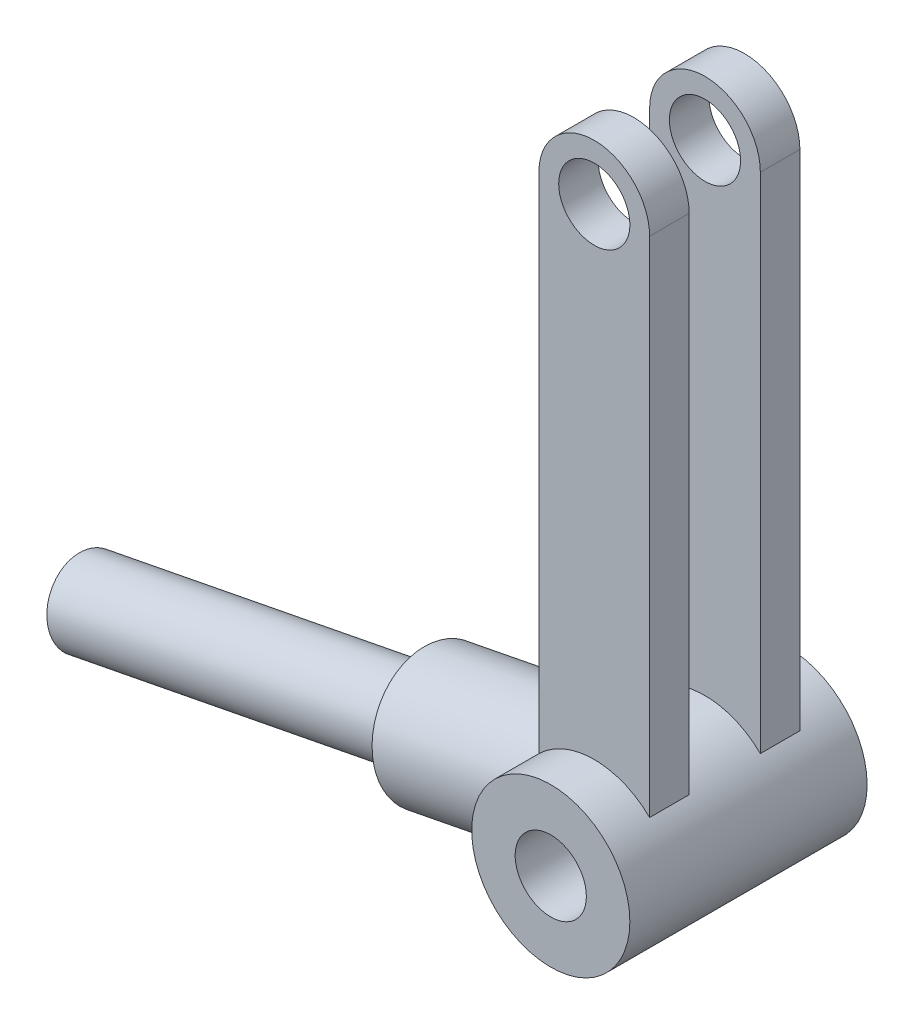
SolidWorks part; units mm, degrees
ref_plane "前视基准面" through (0, 0, 0) normal (0, 0, 1) x (1, 0, 0)
ref_plane "上视基准面" through (0, 0, 0) normal (0, 1, 0) x (1, 0, 0)
ref_plane "右视基准面" through (0, 0, 0) normal (1, 0, 0) x (0, 0, -1)
sketch "草图1" plane through (0, 0, 0) normal (0, 0, 1) x (1, 0, 0)
  circle A0 centre (0, 0) radius 10
  dimension "D1" = 20
extrude "凸台-拉伸1" add sketch "草图1" along normal blind 30
sketch "草图2" plane through (0, 0, 30) normal (0, 0, 1) x (1, 0, 0)
  circle A0 centre (0, 0) radius 4.5
  dimension "D1" = 9
extrude "切除-拉伸1" cut sketch "草图2" against normal blind 30
sketch "草图3" plane through (0, 0, 0) normal (0, 1, 0) x (1, 0, 0)
  line L0 (10, -15) -> (-10, -15) construction
  line L1 (10, -30) -> (10, 0) construction
  line L2 (-10, 0) -> (-10, -30) construction
  line L3 (0, -19.5) -> (7, -19.5)
  line L4 (0, -19.5) -> (-7, -19.5)
  line L5 (0, -10.5) -> (7, -10.5)
  line L6 (0, -10.5) -> (-7, -10.5)
  line L7 (7, -10.5) -> (7, -5.5)
  line L8 (7, -5.5) -> (-7, -5.5)
  line L9 (-7, -5.5) -> (-7, -10.5)
  line L15 (7, -19.5) -> (7, -24.5)
  line L16 (-7, -24.5) -> (-7, -19.5)
  line L17 (7, -24.5) -> (-7, -24.5)
  dimension "D1" = 14
  dimension "D5" = 5
extrude "凸台-拉伸2" add sketch "草图3" along normal blind 66.3 from offset 4.5
sketch "草图4" plane through (0, 0, 5.5) normal (0, 0, -1) x (-1, 0, 0)
  line L0 (-7, 70.8) -> (7, 70.8) construction
  line L1 (-7, 70.8) -> (7, 70.8)
  arc A0 (7, 70.8) -> (-7, 70.8) centre (0, 70.8) ccw
extrude "凸台-拉伸3" add sketch "草图4" against normal blind 5
sketch "草图5" plane through (0, 0, 24.5) normal (0, 0, 1) x (1, 0, 0)
  line L0 (-7, 70.8) -> (7, 70.8) construction
  line L1 (-7, 70.8) -> (7, 70.8)
  arc A0 (7, 70.8) -> (-7, 70.8) centre (0, 70.8) ccw
extrude "凸台-拉伸4" add sketch "草图5" against normal blind 5
sketch "草图6" plane through (0, 0, 5.5) normal (0, 0, -1) x (-1, 0, 0)
  line L0 (-7, 70.8) -> (7, 70.8) construction
  circle A0 centre (0, 70.8) radius 4.5
  dimension "D1" = 9
extrude "切除-拉伸2" cut sketch "草图6" against normal blind 27
sketch "草图14" plane through (0, 0, 5.5) normal (0, 0, -1) x (-1, 0, 0)
  line L2 (4.4175, -0.8579) -> (5.9426, 6.9954)
  line L3 (5.9426, 6.9954) -> (11.3417, 5.9469)
  line L5 (9.8166, -1.9064) -> (11.3417, 5.9469)
  line L6 (4.4175, -0.8579) -> (9.8166, -1.9064)
  circle A2 centre (0, 0) radius 10 construction
  arc A3 (9.8166, -1.9064) -> (7.4151, 6.7095) centre (0, 0) ccw
ref_plane "基准面1" through (0, 0, 15) normal (0, 0, 1) x (1, 0, 0)
sketch "草图15" plane through (0, 0, 15) normal (0, 0, 1) x (1, 0, 0)
  line L1 (-4.4175, -0.8579) -> (-5.9426, 6.9954) construction
  line L5 (-4.4175, -0.8579) -> (-5.9426, 6.9954)
  line L12 (-4.4175, -0.8579) -> (-29.4498, -5.7191)
  line L13 (-5.9426, 6.9954) -> (-30.9749, 2.1342)
  line L14 (-29.4498, -5.7191) -> (-30.9749, 2.1342)
  dimension "D1" = 25.5
revolve "旋转1" add sketch "草图15" angle 360 about L12
sketch "草图17" plane through (-29.4498, -5.7191, 0) normal (-0.9817, -0.1906, 0) x (0, 0, 1)
  circle A0 centre (15, 0) radius 5
  dimension "D1" = 10
extrude "凸台-拉伸9" add sketch "草图17" along normal blind 45
